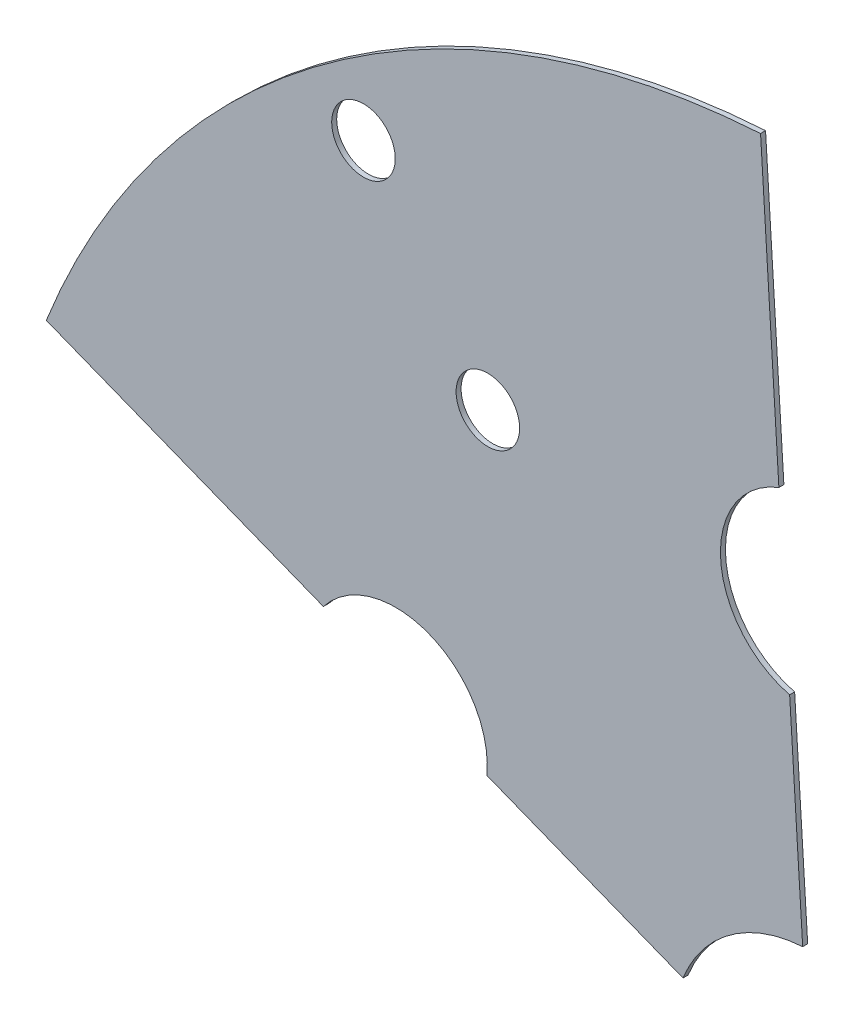
SolidWorks part; units mm, degrees
ref_plane "Front Plane" through (0, 0, 0) normal (0, 0, 1) x (1, 0, 0)
ref_plane "Top Plane" through (0, 0, 0) normal (0, 1, 0) x (1, 0, 0)
ref_plane "Right Plane" through (0, 0, 0) normal (1, 0, 0) x (0, 0, -1)
sketch "Sketch1" plane through (0, 0, 0) normal (0, 0, 1) x (1, 0, 0)
  line L0 (-25.2075, 29.5777) -> (-20.3405, 33.1137)
  line L1 (-22.774, 31.3457) -> (0, 0) construction
  line L2 (0, 0) -> (-50.8, 0) construction
  circle A0 centre (0, 0) radius 50.8
  circle A1 centre (0, 0) radius 38.862 construction
  circle A12 centre (0, 0) radius 19.05 construction
  circle A19 centre (-38.862, 0) radius 9.1764
  circle A20 centre (0, 0) radius 9.7536
  circle A22 centre (-31.44, 22.8425) radius 9.1764
  circle A23 centre (-12.009, 36.96) radius 9.1764
  circle A24 centre (12.009, 36.96) radius 9.1764
  circle A25 centre (31.44, 22.8425) radius 9.1764
  circle A26 centre (38.862, 0) radius 9.1764
  circle A27 centre (31.44, -22.8425) radius 9.1764
  circle A28 centre (12.009, -36.96) radius 9.1764
  circle A29 centre (-12.009, -36.96) radius 9.1764
  circle A30 centre (-31.44, -22.8425) radius 9.1764
  circle A31 centre (-11.1973, 15.4118) radius 9.2964
  circle A32 centre (11.1973, 15.4118) radius 9.2964
  circle A33 centre (18.1176, -5.8868) radius 9.2964
  circle A34 centre (0, -19.05) radius 9.2964
  circle A35 centre (-18.1176, -5.8868) radius 9.2964
  point P27 (0, 0)
  point P32 (0, 0)
  point P43 (0, 0)
  point P49 (0, 0)
  dimension "D1" = 101.6
  dimension "D2" = 11.938
  dimension "D3" = 18.5928
  dimension "D4" = 38.1
  dimension "D5" = 10
  dimension "D6" = 5
sketch "Sketch2" plane through (0, 0, 0) normal (0, 0, 1) x (1, 0, 0)
  circle A0 centre (0, 0) radius 50.165
  circle A1 centre (0, -19.05) radius 9.2964 construction
  circle A2 centre (18.1176, -5.8868) radius 9.2964 construction
  circle A3 centre (11.1973, 15.4118) radius 9.2964 construction
  circle A4 centre (-11.1973, 15.4118) radius 9.2964 construction
  circle A5 centre (-18.1176, -5.8868) radius 9.2964 construction
  circle A6 centre (-38.862, 0) radius 9.1764 construction
  circle A7 centre (-31.44, -22.8425) radius 9.1764 construction
  circle A8 centre (-12.009, -36.96) radius 9.1764 construction
  circle A9 centre (12.009, -36.96) radius 9.1764 construction
  circle A10 centre (31.44, -22.8425) radius 9.1764 construction
  circle A11 centre (38.862, 0) radius 9.1764 construction
  circle A12 centre (31.44, 22.8425) radius 9.1764 construction
  circle A13 centre (12.009, 36.96) radius 9.1764 construction
  circle A14 centre (-12.009, 36.96) radius 9.1764 construction
  circle A15 centre (-31.44, 22.8425) radius 9.1764 construction
  circle A17 centre (0, 0) radius 7.62
  circle A18 centre (0, -19.05) radius 9.2964
  circle A19 centre (18.1176, -5.8868) radius 9.2964
  circle A20 centre (11.1973, 15.4118) radius 9.2964
  circle A21 centre (-11.1973, 15.4118) radius 9.2964
  circle A22 centre (-18.1176, -5.8868) radius 9.2964
  circle A23 centre (-38.862, 0) radius 9.1764
  circle A24 centre (-31.44, -22.8425) radius 9.1764
  circle A25 centre (-12.009, -36.96) radius 9.1764
  circle A26 centre (12.009, -36.96) radius 9.1764
  circle A27 centre (31.44, -22.8425) radius 9.1764
  circle A28 centre (38.862, 0) radius 9.1764
  circle A29 centre (31.44, 22.8425) radius 9.1764
  circle A30 centre (12.009, 36.96) radius 9.1764
  circle A31 centre (-12.009, 36.96) radius 9.1764
  circle A32 centre (-31.44, 22.8425) radius 9.1764
  dimension "D1" = 15.24
  dimension "D2" = 100.33
sketch "Sketch4" plane through (0, 0, 0) normal (0, 0, 1) x (1, 0, 0)
  line L0 (-35.151, 11.4213) -> (-34.2757, 14.1152) construction
  line L1 (-14.0701, 6.5704) -> (-14.6575, 4.7625) construction
  line L2 (0, 0) -> (-47.7098, 15.5018) construction
  line L3 (-2.8326, 36.96) -> (0, 36.96) construction
  line L4 (0, 15.4118) -> (-1.9009, 15.4118) construction
  line L5 (0, 0) -> (0, 50.165) construction
  line L6 (-30.662, 12.096) -> (-18.8481, 7.4355)
  line L7 (-0.5081, 8.2393) -> (-1.2472, 20.2233)
  line L8 (-31.44, 22.8425) -> (-11.1973, 15.4118) construction
  line L9 (-21.3187, 19.1271) -> (-25.3199, 8.2269) construction
  line L10 (0, 0) -> (-11.1973, 15.4118) construction
  line L11 (-2.0289, 32.8992) -> (-3.0331, 49.1826)
  line L12 (-30.662, 12.096) -> (-45.8381, 18.0829)
  line L13 (-7.6791, 3.0294) -> (-18.8481, 7.4355)
  line L14 (-2.0289, 32.8992) -> (-1.2472, 20.2233)
  circle A0 centre (0, 0) radius 50.165 construction
  circle A1 centre (0, 0) radius 50.165 construction
  circle A2 centre (0, 0) radius 7.62 construction
  circle A3 centre (31.44, 22.8425) radius 9.1764 construction
  circle A4 centre (11.1973, 15.4118) radius 9.2964 construction
  circle A5 centre (12.009, 36.96) radius 9.1764 construction
  circle A6 centre (-11.1973, 15.4118) radius 9.2964 construction
  circle A7 centre (-12.009, 36.96) radius 9.1764 construction
  circle A8 centre (-31.44, 22.8425) radius 9.1764 construction
  circle A9 centre (0, 0) radius 7.62
  circle A10 centre (31.44, 22.8425) radius 9.1764
  circle A11 centre (11.1973, 15.4118) radius 9.2964
  circle A12 centre (12.009, 36.96) radius 9.1764
  circle A13 centre (-11.1973, 15.4118) radius 9.2964
  circle A14 centre (-12.009, 36.96) radius 9.1764
  circle A15 centre (-31.44, 22.8425) radius 9.1764
  arc A16 (-0.5081, 8.2393) -> (-7.6791, 3.0294) centre (0, 0) ccw
  arc A17 (-3.0331, 49.1826) -> (-45.8381, 18.0829) centre (0, 0) ccw
  circle A20 centre (0, 0) radius 8.255 construction
  circle A21 centre (0, 0) radius 49.276 construction
  point P33 (-34.2757, 14.1152)
  point P35 (-34.7134, 12.7682)
  point P36 (-14.0701, 6.5704)
  point P37 (-14.3638, 5.6664)
  point P38 (-1.9009, 15.4118)
  point P39 (-0.9505, 15.4118)
  point P40 (-2.8326, 36.96)
  point P41 (-1.4163, 36.96)
  dimension "D3" = 14.0701
  dimension "D1" = 0.635
  dimension "D2" = 0.889
sketch "Sketch5" plane through (0, 0, 0) normal (0, 0, 1) x (1, 0, 0)
  line L0 (-2.0289, 32.8992) -> (-3.0331, 49.1826) construction
  line L1 (-2.0289, 32.8992) -> (-1.2472, 20.2233) construction
  line L2 (-0.5081, 8.2393) -> (-1.2472, 20.2233) construction
  line L3 (-7.6791, 3.0294) -> (-18.8481, 7.4355) construction
  line L4 (-30.662, 12.096) -> (-18.8481, 7.4355) construction
  line L5 (-30.662, 12.096) -> (-45.8381, 18.0829) construction
  line L6 (-2.0289, 32.8992) -> (-3.0331, 49.1826)
  line L7 (-2.0289, 32.8992) -> (-1.2472, 20.2233)
  line L8 (-0.5081, 8.2393) -> (-1.2472, 20.2233)
  line L9 (-7.6791, 3.0294) -> (-18.8481, 7.4355)
  line L10 (-30.662, 12.096) -> (-18.8481, 7.4355)
  line L11 (-30.662, 12.096) -> (-45.8381, 18.0829)
  line L12 (-12.009, 27.7835) -> (-12.009, 24.6727) construction
  line L13 (-12.009, 26.2281) -> (0, 26.2281) construction
  line L14 (0, 0) -> (0, 50.165) construction
  arc A0 (-0.5081, 8.2393) -> (-7.6791, 3.0294) centre (0, 0) ccw construction
  arc A1 (-3.0331, 49.1826) -> (-45.8381, 18.0829) centre (0, 0) ccw construction
  arc A2 (-0.5081, 8.2393) -> (-7.6791, 3.0294) centre (0, 0) ccw
  arc A3 (-3.0331, 49.1826) -> (-45.8381, 18.0829) centre (0, 0) ccw
  circle A4 centre (-12.009, 36.96) radius 9.1764 construction
  circle A5 centre (-11.1973, 15.4118) radius 9.2964 construction
  circle A6 centre (0, 26.2281) radius 3.175 construction
  circle A7 centre (24.9444, 8.1049) radius 3.175 construction
  circle A8 centre (15.4165, -21.219) radius 3.175 construction
  circle A9 centre (-15.4165, -21.219) radius 3.175 construction
  circle A10 centre (-24.9444, 8.1049) radius 3.175 construction
  point P31 (0, 0)
  dimension "D1" = 6.35
  dimension "D2" = 5
extrude "Boss-Extrude1" add sketch "Sketch5" along normal blind 0.3
sketch "Sketch7" plane through (0, 0, 0) normal (0, 0, -1) x (-1, 0, 0)
  circle A0 centre (26.8311, 36.9249) radius 1.905
  circle A1 centre (19.3758, 26.6636) radius 1.905
extrude "Cut-Extrude3" cut sketch "Sketch7" against normal through all
sketch "Sketch8" plane through (0, 0, 0) normal (0, 0, -1) x (-1, 0, 0)
  line L0 (0.5081, 8.2393) -> (3.0331, 49.1826) construction
  line L1 (45.8381, 18.0829) -> (7.6791, 3.0294) construction
  line L2 (1.2903, 20.923) -> (1.934, 31.36)
  line L3 (29.2331, 11.5323) -> (19.4323, 7.666)
  arc A0 (29.2331, 11.5323) -> (19.4323, 7.666) centre (24.8958, 8.1719) ccw
  arc A1 (1.2903, 20.923) -> (1.934, 31.36) centre (-0.0486, 26.2439) ccw
  dimension "D1" = 5.4868
extrude "Cut-Extrude4" cut sketch "Sketch8" against normal through all
